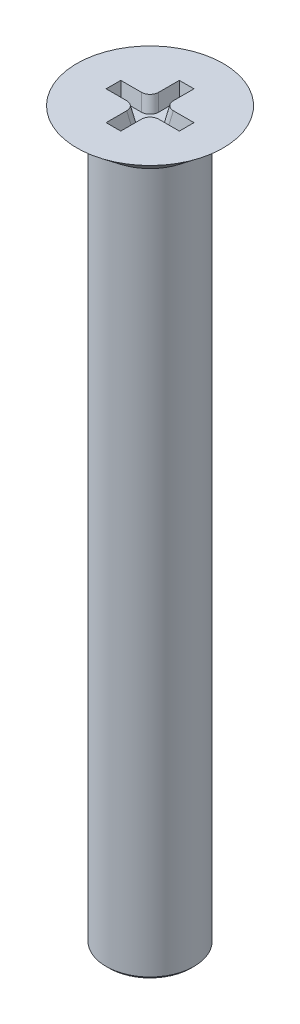
SolidWorks part; units mm, degrees
material "AISI 321 退火不锈钢 (SS)"
ref_plane "前视基准面" through (0, 0, 0) normal (0, 0, 1) x (1, 0, 0)
ref_plane "上视基准面" through (0, 0, 0) normal (0, 1, 0) x (1, 0, 0)
ref_plane "右视基准面" through (0, 0, 0) normal (1, 0, 0) x (0, 0, -1)
other "Configuration Table"
sketch "草图1" plane through (0, 0, 0) normal (0, 0, 1) x (1, 0, 0)
  line L0 (0, 0) -> (2.5, 0)
  line L1 (2.5, 0) -> (1.5, -0.8)
  line L2 (1.5, -0.8) -> (0, -0.8)
  line L3 (0, -0.8) -> (0, 0)
  dimension "D1" = 2.5
  dimension "D2" = 0.8
  dimension "D3" = 1.5
revolve "旋转1" add sketch "草图1" angle 360 about L3
sketch "草图2" plane through (0, -0.8, 0) normal (0, -1, 0) x (1, 0, 0)
  circle A1 centre (0, 0) radius 1.5
  circle A2 centre (0, 0) radius 1.5
  dimension "D1" = 0
extrude "凸台-拉伸1" add sketch "草图2" along normal blind 24
cosmetic thread "装饰螺纹线1" parameters "D2"=2.459
chamfer "倒角1" distance 0.1 angle 45 1 edges at (0, -24.8, -1.5)
sketch "草图3" plane through (0, 0, 0) normal (0, 1, 0) x (1, 0, 0)
  line L1 (-1.25, -0.25) -> (1.25, -0.25)
  line L2 (-1.25, -0.25) -> (-1.25, 0.25)
  line L3 (-1.25, 0.25) -> (1.25, 0.25)
  line L4 (1.25, -0.25) -> (1.25, 0.25)
  line L5 (-1.25, -0.25) -> (1.25, 0.25) construction
  line L6 (-1.25, 0.25) -> (1.25, -0.25) construction
  line L7 (-0.25, 1.25) -> (0.25, 1.25)
  line L8 (-0.25, 1.25) -> (-0.25, -1.25)
  line L9 (-0.25, -1.25) -> (0.25, -1.25)
  line L10 (0.25, 1.25) -> (0.25, -1.25)
  line L11 (-0.25, 1.25) -> (0.25, -1.25) construction
  line L12 (-0.25, -1.25) -> (0.25, 1.25) construction
  point P0 (0, 0)
  point P6 (0, 0)
  dimension "D1" = 0.5
  dimension "D2" = 0.5
  dimension "D3" = 2.5
  dimension "D4" = 2.5
extrude "切除-拉伸1" cut sketch "草图3" against normal blind 0.5 draft 10 contours L3 L10 L1 L4 | L10 L7 L8 L3 | L8 L3 L2 L1 | L10 L3 L8 L1 | L10 L1 L8 L9
fillet "圆角1" radius 0.3 4 edges at (-0.2059, -0.25, -0.2059) (0.2059, -0.25, -0.2059) (-0.2059, -0.25, 0.2059) (0.2059, -0.25, 0.2059)
